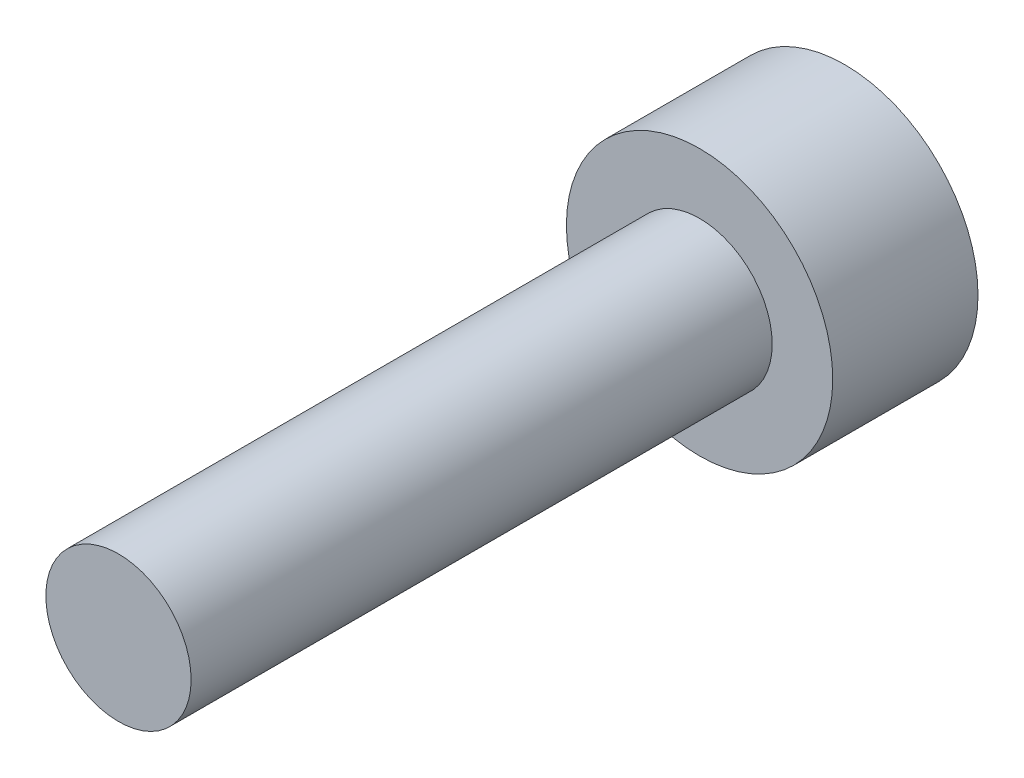
SolidWorks part; units mm, degrees
material "Acero aleado"
ref_plane "Alzado" through (0, 0, 0) normal (0, 0, 1) x (1, 0, 0)
ref_plane "Planta" through (0, 0, 0) normal (0, 1, 0) x (1, 0, 0)
ref_plane "Vista lateral" through (0, 0, 0) normal (1, 0, 0) x (0, 0, -1)
sketch "Croquis1" plane through (0, 0, 0) normal (0, 0, 1) x (1, 0, 0)
  circle A0 centre (0, 0) radius 2.75
  dimension "D1" = 5.5
extrude "Cabeza" add sketch "Croquis1" along normal blind 3 from offset 3
sketch "Croquis2" plane through (0, 0, 0) normal (0, 0, 1) x (1, 0, 0)
  circle A0 centre (0, 0) radius 1.5
  dimension "D1" = 3
extrude "Cuerpo" add sketch "Croquis2" along normal blind 12
sketch "Croquis3" plane through (0, 0, 0) normal (0, 0, 1) x (1, 0, 0)
  line L0 (1.4434, 0) -> (0.7217, 1.25)
  line L1 (0.7217, 1.25) -> (-0.7217, 1.25)
  line L2 (-0.7217, 1.25) -> (-1.4434, 0)
  line L3 (-1.4434, 0) -> (-0.7217, -1.25)
  line L4 (-0.7217, -1.25) -> (0.7217, -1.25)
  line L5 (0.7217, -1.25) -> (1.4434, 0)
  dimension "D1" = 1.4434
  dimension "D2" = 0.7217
  dimension "D3" = 1.25
  dimension "D4" = 0.7217
  dimension "D5" = 1.25
  dimension "D6" = 1.4434
  dimension "D7" = 0.7217
  dimension "D8" = 1.25
  dimension "D9" = 0.7217
  dimension "D10" = 1.25
extrude "Hexagono_interior" cut sketch "Croquis3" along normal blind 1.3 from offset 3
